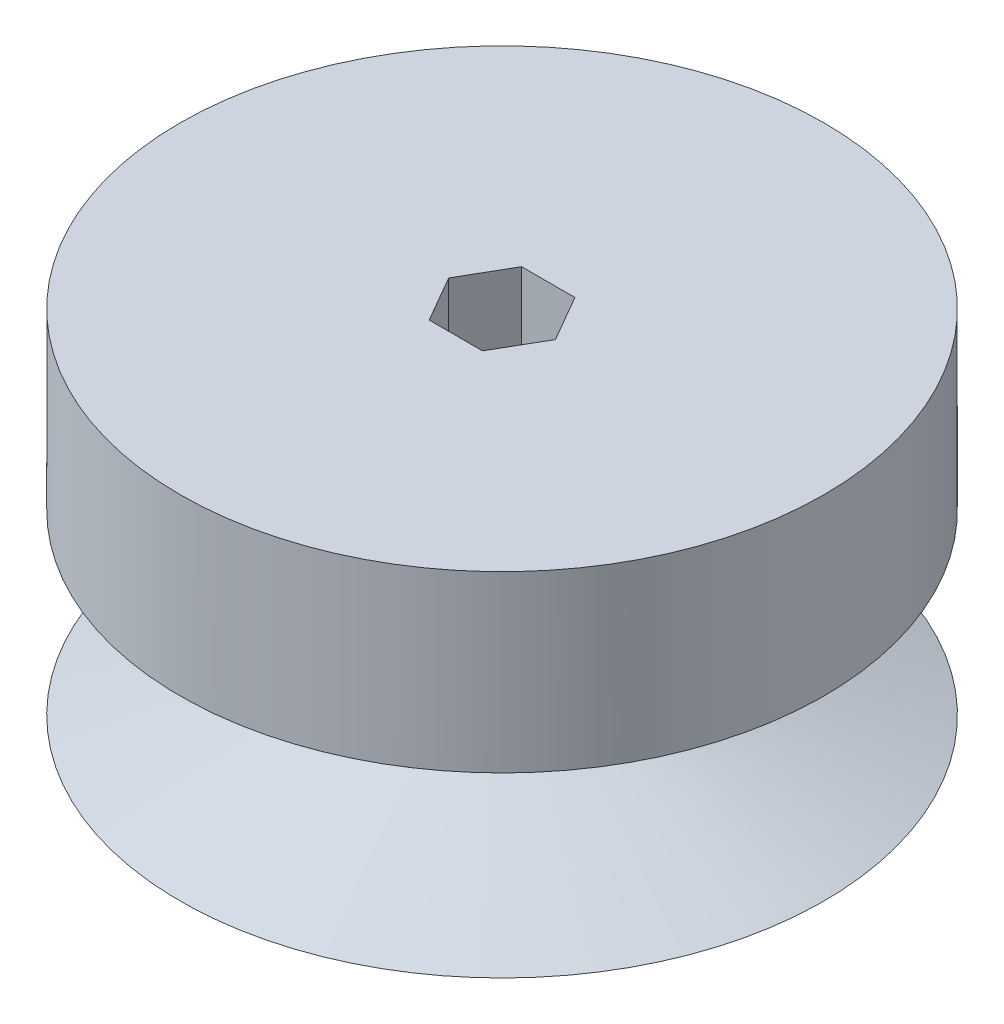
SolidWorks part; units mm, degrees
material "Gray Cast Iron"
ref_plane "Front Plane" through (0, 0, 0) normal (0, 0, 1) x (1, 0, 0)
ref_plane "Top Plane" through (0, 0, 0) normal (0, 1, 0) x (1, 0, 0)
ref_plane "Right Plane" through (0, 0, 0) normal (1, 0, 0) x (0, 0, -1)
sketch "Sketch1" plane through (0, 0, 0) normal (0, 1, 0) x (1, 0, 0)
  circle A0 centre (0, 0) radius 44.25
  dimension "D1" = 88.5
ref_plane "Plane1" through (0, 12, 0) normal (0, 1, 0) x (1, 0, 0)
sketch "Sketch2" plane through (0, 12, 0) normal (0, 1, 0) x (1, 0, 0)
  circle A0 centre (0, 0) radius 12
  dimension "D1" = 24
loft "Loft1" add profiles "Sketch2", "Sketch1"
sketch "Sketch4" plane through (0, 12, 0) normal (0, 1, 0) x (1, 0, 0)
  circle A0 centre (0, 0) radius 12
  dimension "D1" = 24
ref_plane "Plane2" through (0, 12.2, 0) normal (0, 1, 0) x (1, 0, 0)
mirror "Mirror2" about plane through (0, 12.2, 0) normal (0, 1, 0) of bodies 101
sketch "Sketch6" plane through (0, 24.4, 0) normal (0, 1, 0) x (1, 0, 0)
  circle A0 centre (0, 0) radius 44.25
extrude "Boss-Extrude1" add sketch "Sketch6" along normal blind 23.956
sketch "Sketch7" plane through (0, 48.356, 0) normal (0, 1, 0) x (1, 0, 0)
  line L1 (7.3323, 0) -> (3.6662, 6.35)
  line L2 (3.6662, 6.35) -> (-3.6662, 6.35)
  line L3 (-3.6662, 6.35) -> (-7.3323, 0)
  line L4 (-7.3323, 0) -> (-3.6662, -6.35)
  line L5 (-3.6662, -6.35) -> (3.6662, -6.35)
  line L6 (3.6662, -6.35) -> (7.3323, 0)
  circle A0 centre (0, 0) radius 6.35 construction
  dimension "D1" = 12.7
extrude "Cut-Extrude1" cut sketch "Sketch7" against normal through all
